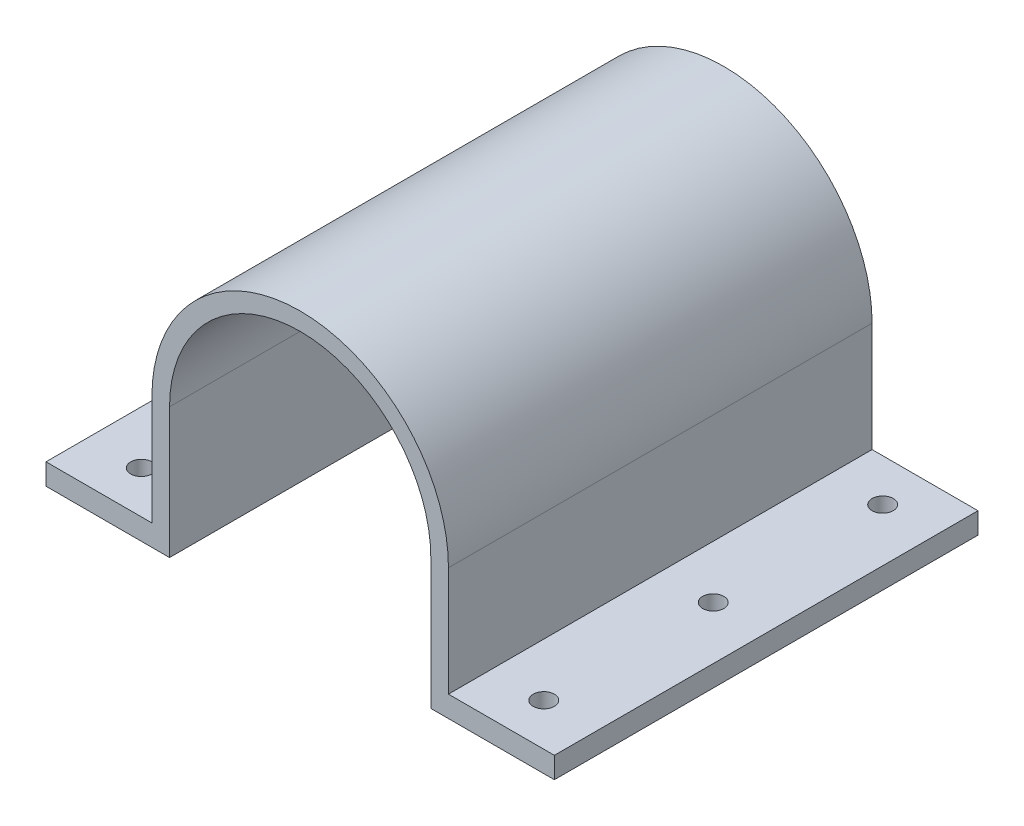
SolidWorks part; units mm, degrees
ref_plane "Front Plane" through (0, 0, 0) normal (0, 0, 1) x (1, 0, 0)
ref_plane "Top Plane" through (0, 0, 0) normal (0, 1, 0) x (1, 0, 0)
ref_plane "Right Plane" through (0, 0, 0) normal (1, 0, 0) x (0, 0, -1)
sketch "Sketch1" plane through (0, 0, 0) normal (0, 0, 1) x (1, 0, 0)
  line L0 (-21, 0) -> (-21, -15.5)
  line L1 (-21, -15.5) -> (-36, -15.5)
  line L2 (-36, -15.5) -> (-36, -18.5)
  line L3 (-36, -18.5) -> (36, -18.5)
  line L4 (36, -18.5) -> (36, -15.5)
  line L5 (36, -15.5) -> (21, -15.5)
  line L6 (21, -15.5) -> (21, 0)
  line L7 (0, 0) -> (0, 7) construction
  line L8 (0, 0) -> (-15.5, 0) construction
  line L9 (-21, -15.5) -> (21, -15.5) construction
  arc A0 (21, 0) -> (-21, 0) centre (0, 0) ccw
  circle A2 centre (-15.5, 0) radius 1.65
  circle A3 centre (-7.75, 13.4234) radius 1.65
  circle A4 centre (7.75, 13.4234) radius 1.65
  circle A5 centre (15.5, 0) radius 1.65
  circle A6 centre (7.75, -13.4234) radius 1.65
  circle A7 centre (-7.75, -13.4234) radius 1.65
  circle A8 centre (0, 0) radius 18.5 construction
  circle A9 centre (0, 7) radius 6.15
  point P15 (0, -18.5)
  point P27 (0, 0)
  dimension "D1" = 42
  dimension "D6" = 0
  dimension "D7" = 3.3
  dimension "D10" = 37
  dimension "D11" = 2.5
  dimension "D3" = 12.3
  dimension "D2" = 7
  dimension "D4" = 72
  dimension "D5" = 3
  dimension "D8" = 15.5
  dimension "D9" = 6
extrude "Boss-Extrude1" add sketch "Sketch1" along normal blind 60
sketch "Sketch2" plane through (0, 0, 60) normal (0, 0, 1) x (1, 0, 0)
  line L0 (-18.5, 0) -> (-18.5, -18.5)
  line L1 (-36, -18.5) -> (36, -18.5) construction
  line L2 (-18.5, -18.5) -> (18.5, -18.5)
  line L3 (18.5, -18.5) -> (18.5, 0)
  arc A0 (18.5, 0) -> (-18.5, 0) centre (0, 0) ccw
  arc A1 (-18.5, 0) -> (18.5, 0) centre (0, 0) ccw construction
  dimension "D1" = 37
extrude "Cut-Extrude1" cut sketch "Sketch2" against normal blind 57
sketch "Sketch3" plane through (0, -15.5, 0) normal (0, 1, 0) x (1, 0, 0)
  line L0 (0, 0) -> (0, -60) construction
  line L1 (-21, -60) -> (21, -60) construction
  line L2 (-28.5, 0) -> (-28.5, -60) construction
  line L3 (-21, 0) -> (-36, 0) construction
  line L4 (-21, -60) -> (-36, -60) construction
  circle A0 centre (-28.5, -30) radius 1.5
  circle A1 centre (-28.5, -6) radius 1.5
  circle A2 centre (-28.5, -54) radius 1.5
  circle A3 centre (28.5, -54) radius 1.5
  circle A4 centre (28.5, -6) radius 1.5
  circle A5 centre (28.5, -30) radius 1.5
  dimension "D1" = 24
  dimension "D2" = 24
  dimension "D3" = 3
extrude "Cut-Extrude2" cut sketch "Sketch3" against normal through all
